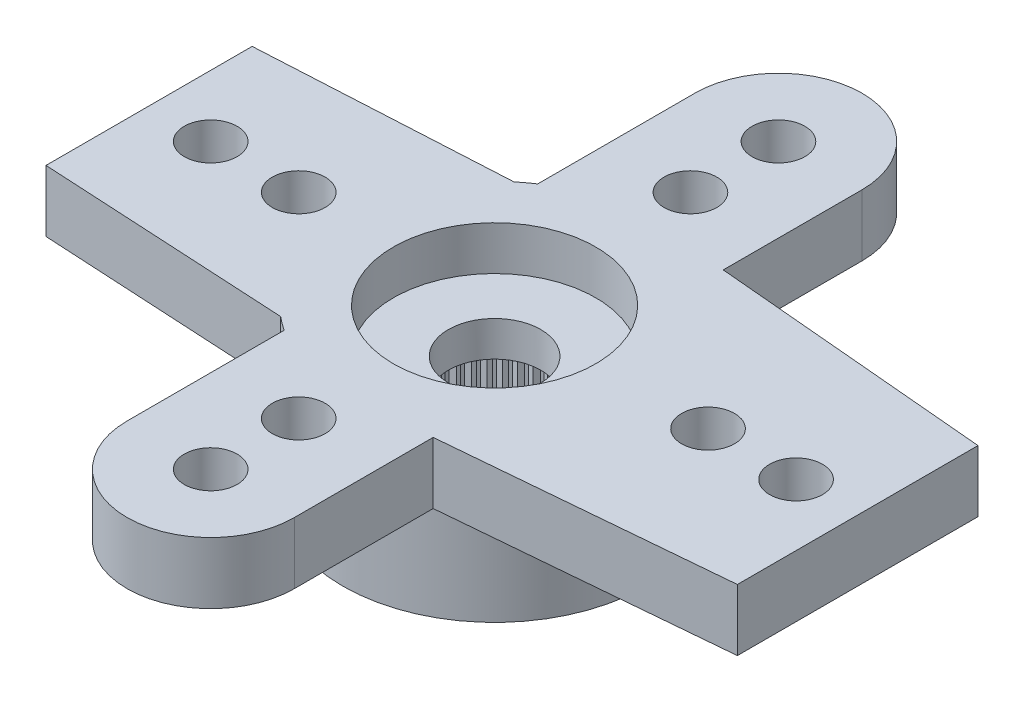
SolidWorks part; units mm, degrees
material "PVC Rígido"
ref_plane "Plano frontal" through (0, 0, 0) normal (0, 0, 1) x (1, 0, 0)
ref_plane "Plano superior" through (0, 0, 0) normal (0, 1, 0) x (1, 0, 0)
ref_plane "Plano direito" through (0, 0, 0) normal (1, 0, 0) x (0, 0, -1)
sketch "Esboço1" plane through (0, 0, 0) normal (0, 1, 0) x (1, 0, 0)
  line L0 (0, 0) -> (-14.05, 0) construction
  line L1 (-14.1591, 1.997) -> (-2.2091, 2.65)
  line L2 (-2.2091, -2.65) -> (-14.1591, -1.997)
  arc A0 (-2.2091, -2.65) -> (-2.2091, 2.65) centre (0, 0) ccw
  arc A1 (-14.1591, 1.997) -> (-14.1591, -1.997) centre (-14.05, 0) ccw
  dimension "D1" = 6.9
  dimension "D2" = 4
  dimension "D3" = 19.5
  dimension "D4" = 5.3
extrude "Ressalto-extrusão1" add sketch "Esboço1" against normal blind 1.4
sketch "Esboço2" plane through (0, -1.4, 0) normal (0, -1, 0) x (1, 0, 0)
  arc A0 (-2.2091, -2.65) -> (-2.2091, 2.65) centre (0, 0) ccw construction
  circle A1 centre (0, 0) radius 3.45
extrude "Ressalto-extrusão2" add sketch "Esboço2" along normal offset from surface (2.4 mm away) 3.8 up to face at (-7.242, 0, 0)
hole_wizard "Furo1" positions "Esboço9" profile "Esboço10" legacy end condition through all
sketch "Esboço9" plane through (0, 0, 0) normal (0, 1, 0) x (1, 0, 0)
  line L1 (-14.45, 0) -> (0, 0) construction
  arc A2 (-14.1591, 1.997) -> (-14.1591, -1.997) centre (-14.05, 0) ccw construction
  point P0 (-14.45, 0)
  point P19 (-16.05, 0)
  dimension "D1" = 1.6
sketch "Esboço10" plane through (-14.45, 0, 0) normal (1, 0, 0) x (0, 0, 1)
  line L0 (0, 0) -> (0, 3.8)
  line L1 (0, 3.8) -> (0.6, 3.8)
  line L2 (0.6, 3.8) -> (0.6, 0)
  line L3 (0.6, 0) -> (0, 0)
  line L4 (0, 110) -> (0, -10) construction
  dimension "Diameter" = 1.2
  dimension "Depth" = 3.8
pattern_linear "Padrão linear1" count 6 spacing 2 along (1, 0, 0) of "Furo1"
sketch "Esboço12" plane through (0, 0, 0) normal (0, 1, 0) x (1, 0, 0)
  line L0 (0.3041, 3.4366) -> (16.6263, 1.9922)
  line L1 (16.6263, -1.9922) -> (0.3041, -3.4366)
  arc A0 (-2.2091, -2.65) -> (-2.2091, 2.65) centre (0, 0) ccw construction
  arc A1 (0.3041, -3.4366) -> (0.3041, 3.4366) centre (0, 0) ccw
  arc A2 (16.6263, 1.9922) -> (16.6263, -1.9922) centre (16.45, 0) cw
  arc A3 (-14.1591, 1.997) -> (-14.1591, -1.997) centre (-14.05, 0) ccw construction
  dimension "D1" = 2
  dimension "D2" = 34.5
extrude "Ressalto-extrusão3" add sketch "Esboço12" against normal up to surface (1.4 mm away) up to face at (-12.45, -1.4, 0.6)
hole_wizard "Furo2" positions "Esboço13" profile "Esboço14" legacy end condition through all
sketch "Esboço13" plane through (0, 0, 0) normal (0, 1, 0) x (1, 0, 0)
  line L0 (0, 0) -> (16.85, 0) construction
  arc A0 (16.6263, -1.9922) -> (16.6263, 1.9922) centre (16.45, 0) ccw construction
  point P0 (16.85, 0)
  point P6 (18.45, 0)
  dimension "D1" = 1.6
sketch "Esboço14" plane through (16.85, 0, 0) normal (1, 0, 0) x (0, 0, 1)
  line L0 (0, 0) -> (0, 3.8)
  line L1 (0, 3.8) -> (0.6, 3.8)
  line L2 (0.6, 3.8) -> (0.6, 0)
  line L3 (0.6, 0) -> (0, 0)
  line L4 (0, 110) -> (0, -10) construction
  dimension "Diameter" = 1.2
  dimension "Depth" = 3.8
pattern_linear "Padrão linear2" count 7 spacing 2 along (-1, 0, 0) of "Furo2"
sketch "Esboço16" plane through (0, 0, 0) normal (0, 1, 0) x (1, 0, 0)
  line L0 (0, -6.45) -> (0, 6.45) construction
  line L1 (-1.9, -6.45) -> (-1.9, 6.45)
  line L2 (1.9, -6.45) -> (1.9, 6.45)
  arc A0 (-1.9, -6.45) -> (1.9, -6.45) centre (0, -6.45) ccw
  arc A1 (1.9, 6.45) -> (-1.9, 6.45) centre (0, 6.45) ccw
  point P2 (0, 0)
  dimension "D2" = 16.7
  dimension "D1" = 3.8
extrude "Ressalto-extrusão4" add sketch "Esboço16" against normal up to surface (1.4 mm away) up to face at (14.85, -1.4, 0.6)
hole_wizard "Furo3" positions "Esboço17" profile "Esboço18" legacy end condition through all
sketch "Esboço17" plane through (0, 0, 0) normal (0, 1, 0) x (1, 0, 0)
  point P0 (0, -6.45)
sketch "Esboço18" plane through (0, 0, 6.45) normal (1, 0, 0) x (0, 0, 1)
  line L0 (0, 0) -> (0, 3.8)
  line L1 (0, 3.8) -> (0.6, 3.8)
  line L2 (0.6, 3.8) -> (0.6, 0)
  line L3 (0.6, 0) -> (0, 0)
  line L4 (0, 110) -> (0, -10) construction
  dimension "Diameter" = 1.2
  dimension "Depth" = 3.8
pattern_linear "Padrão linear3" count 2 spacing 2 along (0, 0, -1) of "Furo3"
pattern_circular "PadrãoCircular1" count 2 over 360 about axis through (0, 0, 0) along (0, 1, 0) of "Padrão linear3", "Furo3"
hole_wizard "Furo4" positions "Esboço3" profile "Esboço4" legacy
sketch "Esboço3" plane through (0, -3.8, 0) normal (0, -1, 0) x (-1, 0, 0)
  point P0 (0, 0)
sketch "Esboço4" plane through (0, -3.8, 0) normal (1, 0, 0) x (0, 0, -1)
  line L0 (0, 0) -> (0, 2)
  line L1 (0, 2) -> (2.475, 2)
  line L2 (2.475, 2) -> (2.475, 0)
  line L3 (2.475, 0) -> (0, 0)
  line L4 (0, 110) -> (0, -10) construction
  dimension "Diameter" = 4.95
  dimension "Depth" = 2
hole_wizard "Furo5" positions "Esboço5" profile "Esboço6" legacy
sketch "Esboço5" plane through (0, 0, 0) normal (0, 1, 0) x (1, 0, 0)
  point P0 (0, 0)
sketch "Esboço6" plane through (0, 0, 0) normal (1, 0, 0) x (0, 0, 1)
  line L0 (0, 0) -> (0, 1)
  line L1 (0, 1) -> (2.3, 1)
  line L2 (2.3, 1) -> (2.3, 0)
  line L3 (2.3, 0) -> (0, 0)
  line L4 (0, 110) -> (0, -10) construction
  dimension "Diameter" = 4.6
  dimension "Depth" = 1
hole_wizard "Furo6" positions "Esboço7" profile "Esboço8" legacy end condition through all
sketch "Esboço7" plane through (0, 0, 0) normal (0, 1, 0) x (1, 0, 0)
  point P0 (0, 0)
sketch "Esboço8" plane through (0, 0, 0) normal (1, 0, 0) x (0, 0, 1)
  line L0 (0, 0) -> (0, 3.8)
  line L1 (0, 3.8) -> (1.05, 3.8)
  line L2 (1.05, 3.8) -> (1.05, 0)
  line L3 (1.05, 0) -> (0, 0)
  line L4 (0, 110) -> (0, -10) construction
  dimension "Diameter" = 2.1
  dimension "Depth" = 3.8
sketch "Esboço11" plane through (0, -3.8, 0) normal (0, -1, 0) x (1, 0, 0)
  line L0 (-0.0981, 2.4731) -> (0, 2.375)
  line L1 (0, 2.375) -> (0.0981, 2.4731)
  line L2 (0, 0) -> (0, 2.475) construction
  circle A0 centre (0, 0) radius 2.375 construction
  circle A1 centre (0, 0) radius 2.475
  arc A2 (0.0981, 2.4731) -> (-0.0981, 2.4731) centre (0, 0) ccw
  dimension "D3" = 4.75
  dimension "D2" = 0.1
  dimension "D1" = 0
extrude "Ressalto-extrusão5" add sketch "Esboço11" against normal up to surface (2 mm away) up to face at (0, -1.8, 1.05)
pattern_circular "PadrãoCircular2" count 60 over 360 about axis through (0, 0, 0) along (0, 1, 0) of "Ressalto-extrusão5"
sketch "Sketch1" plane through (0, 0, 0) normal (0, 1, 0) x (1, 0, 0)
  line L0 (-7.85, 2.3418) -> (-7.85, -2.3418)
  line L1 (-2.2091, 2.65) -> (-14.1591, 1.997) construction
  line L2 (-14.1591, -1.997) -> (-2.2091, -2.65) construction
  line L3 (-7.85, -2.3418) -> (-20.5712, -2.3418)
  line L4 (-20.5712, -2.3418) -> (-20.5712, 2.3017)
  line L5 (-20.5712, 2.3017) -> (-7.85, 2.3418)
  line L6 (8.25, 2.7334) -> (8.25, -2.7334)
  line L7 (16.6263, 1.9922) -> (1.9, 3.2953) construction
  line L8 (1.9, -3.2953) -> (16.6263, -1.9922) construction
  line L9 (8.25, -2.7334) -> (21.3234, -2.7334)
  line L10 (21.3234, -2.7334) -> (21.3234, 2.573)
  line L11 (21.3234, 2.573) -> (8.25, 2.7334)
  circle A0 centre (-8.45, 0) radius 0.6 construction
  circle A1 centre (8.85, 0) radius 0.6 construction
  point P14 (-7.85, 0)
  point P19 (8.25, 0)
extrude "Cut-Extrude3" cut sketch "Sketch1" against normal blind 10
